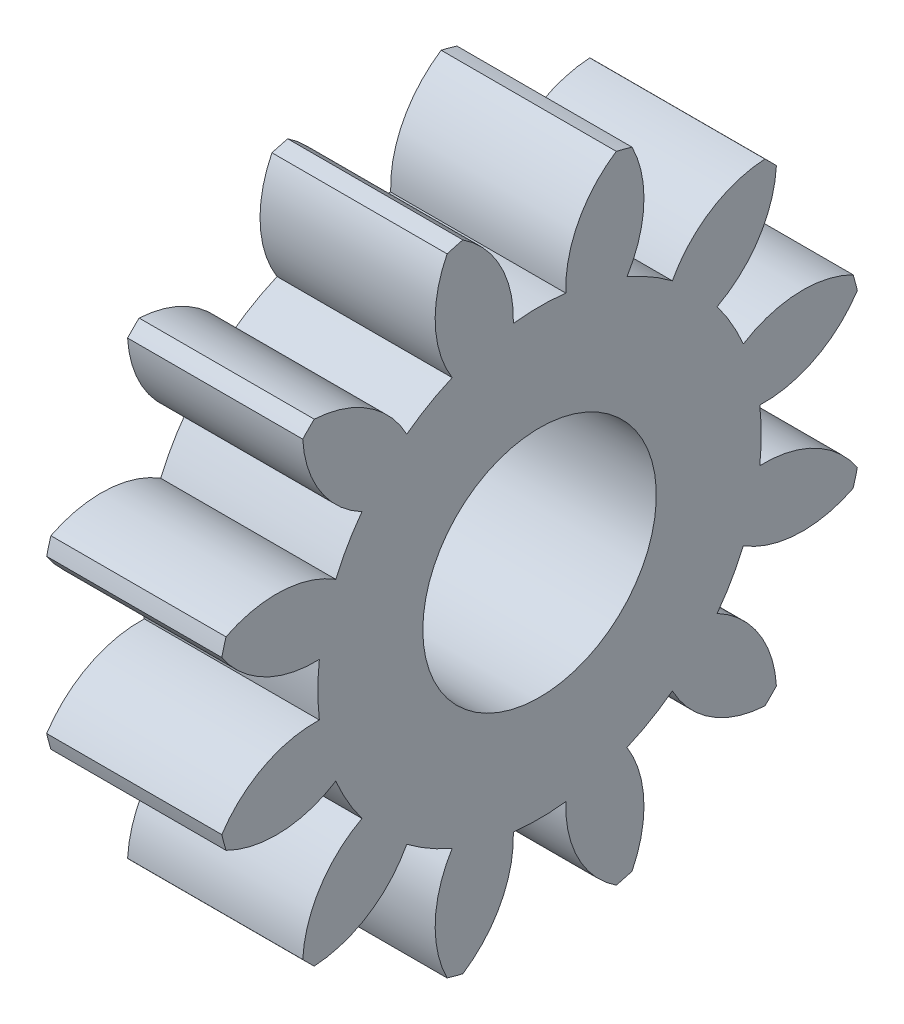
SolidWorks part; units mm, degrees
ref_plane "Plane1" through (0, 0, 0) normal (0, 0, 1) x (1, 0, 0)
ref_plane "Plane2" through (0, 0, 0) normal (0, 1, 0) x (1, 0, 0)
ref_plane "Plane3" through (0, 0, 0) normal (1, 0, 0) x (0, 0, -1)
sketch "HoldingSke" plane through (0, 0, 0) normal (0, 1, 0) x (1, 0, 0)
  line L0 (0, 0) -> (1.2227, -0.2599)
  line L1 (-15, 0) -> (100, 0) construction
  line L2 (0, 0) -> (-2.1039, 2.3779)
  line L3 (0, 0) -> (-11.863, 4.5341)
  line L4 (0, 0) -> (8.4473, 1.7955)
  line L5 (0, 0) -> (-46.8476, -17.4728)
  line L6 (0, 0) -> (-9.9476, -6.7116)
  line L7 (-2.1039, 2.3779) -> (8.6586, 51.2059)
  line L8 (-76.2, 54.61) -> (-75.5, 54.61)
  line L9 (-71.009, 38.7566) -> (-53.1078, 45.2721)
  line L10 (-76.2, 71.12) -> (104.1128, 71.12)
  line L11 (0, 0) -> (-12, 0)
  line L12 (-76.2, 101.6) -> (-76.17, 101.6)
  line L13 (24.9733, 27.94) -> (52.9518, 28.4284)
  line L14 (24.9733, 27.94) -> (24.9743, 27.94)
  line L15 (24.9733, 27.94) -> (100.4006, 29.5858)
  line L16 (-63.627, -0.8) -> (-12.827, -0.8)
  circle A0 centre (0, 0) radius 2
  circle A1 centre (0, 0) radius 3.799
  circle A2 centre (0, 0) radius 37.5
  circle A3 centre (0, 0) radius 2
  dimension "MHD" = 7.598
  dimension "Hub_dia" = 75
  dimension "Bore" = 4
  dimension "MBD" = 4
  dimension "Num_teeth" = 12
  dimension "Pitch" = 1.25
  dimension "Overall_len" = 50
  dimension "Show_teeth" = 12
  dimension "Thickness" = 12
  dimension "OAL" = 50.0001
  dimension "T_dim" = 0.7
  dimension "Ap" = 20
  dimension "H" = 19.05
  dimension "Pitch_radius" = 180.3128
  dimension "Width" = 12
  dimension "Backlash" = 0.03
  dimension "Addendum_fac" = 1
  dimension "Dedendum_fac" = 1.25
  dimension "Clearance_fac" = 0.25
  dimension "Dedendum_add" = 0.001
  dimension "Module" = 0.8
sketch "BasProSke" plane through (0, 0, 0) normal (0, 1, 0) x (1, 0, 0)
  line L0 (-10, 0) -> (60, 0) construction
  line L1 (0, 0) -> (0, 5.6)
  line L2 (0, 0) -> (12, 0)
  line L3 (12, 0) -> (12, 5.6)
  line L4 (12, 5.6) -> (0, 5.6)
  dimension "Thickness" = 12
  dimension "Diameter" = 11.2
revolve "Base-Revolve" add sketch "BasProSke" angle 360 about L0
sketch "TooCutSke" plane through (0, 0, 0) normal (1, 0, 0) x (0, 0, -1)
  line L1 (0, 0) -> (0, 107) construction
  line L2 (0, 0) -> (-0.6789, 4.7517) construction
  line L3 (0, 0) -> (-2.4668, 9.2063) construction
  line L4 (-0.6789, 4.7517) -> (-1.2334, 4.6032) construction
  arc A0 (0.4492, 3.7723) -> (-0.4492, 3.7723) centre (0, 0) ccw
  arc A1 (1.3434, 5.4626) -> (-1.3434, 5.4626) centre (0, 0) ccw
  circle A2 centre (0, 0) radius 4.8 construction
  circle A3 centre (0, 0) radius 4.5105 construction
  arc A4 (-0.4492, 3.7723) -> (-1.3434, 5.4626) centre (-2.3681, 3.8389) ccw
  arc A5 (1.3434, 5.4626) -> (0.4492, 3.7723) centre (2.3681, 3.8389) ccw
  dimension "Root_dia" = 7.598
  dimension "Overcut_dia" = 11.2508
  dimension "Pitch_dia" = 9.6
  dimension "Base_dia" = 9.021
  dimension "Flank_rad" = 1.92
  dimension "Half_ang" = 15
  dimension "Half_CT" = 0.574
extrude "ToothCut" cut sketch "TooCutSke" along normal through all
fillet "Breaks" [suppressed] radius 0.016
fillet "RootFillets" [suppressed] radius 0.201
pattern_circular "TeethCuts" count 12 every 30 about axis through (-10, 0, 0) along (1, 0, 0) of "ToothCut", "RootFillets", "Breaks"
sketch "HubNeaOneSke" plane through (0, 0, 0) normal (-1, 0, 0) x (0, 0, 1)
  circle A0 centre (0, 0) radius 3.799
  dimension "Diameter" = 7.598
extrude "HubNearOne" [suppressed] add sketch "HubNeaOneSke" along normal blind 38.0001
sketch "HubNeaBotSke" plane through (0, 0, 0) normal (-1, 0, 0) x (0, 0, 1)
  circle A0 centre (0, 0) radius 3.799
  dimension "Diameter" = 7.598
extrude "HubNearBoth" [suppressed] add sketch "HubNeaBotSke" along normal blind 19
ref_plane "FarPln" through (12, 0, 0) normal (1, 0, 0) x (0, 0, -1)
sketch "HubFarSke" plane through (12, 0, 0) normal (1, 0, 0) x (0, 0, -1)
  circle A0 centre (0, 0) radius 3.799
  dimension "Diameter" = 7.598
extrude "HubFar" [suppressed] add sketch "HubFarSke" along normal blind 19
sketch "BorSke" plane through (0, 0, 0) normal (1, 0, 0) x (0, 0, -1)
  circle A0 centre (0, 0) radius 2
  dimension "Diameter" = 4
extrude "Bore" cut sketch "BorSke" along normal mid plane 100.0001
sketch "KeySke" plane through (0, 0, 0) normal (1, 0, 0) x (0, 0, -1)
  line L0 (-0.8, 0) -> (-0.8, 2.7)
  line L1 (-0.8, 2.7) -> (0.8, 2.7)
  line L2 (0.8, 2.7) -> (0.8, 0)
  line L3 (0, 0) -> (0, 34) construction
  line L4 (-0.8, 0) -> (0.8, 0)
  dimension "Offset" = 2.7
  dimension "Width" = 1.6
extrude "Keyway" [suppressed] cut sketch "KeySke" along normal mid plane 100.0001
pattern_circular "Keyway2" [suppressed] count 2 every 90 about axis through (-10, 0, 0) along (1, 0, 0)
sketch "Croquis1" plane through (0, 0, 0) normal (-1, 0, 0) x (0, 0, 1)
  line L1 (-5.9657, 6.0317) -> (6.45, 6.0317)
  line L2 (-5.9657, 6.0317) -> (-5.9657, -5.7235)
  line L3 (-5.9657, -5.7235) -> (6.45, -5.7235)
  line L4 (6.45, 6.0317) -> (6.45, -5.7235)
extrude "Cortar-Extruir1" cut sketch "Croquis1" against normal blind 9
equation "' \"Module@HoldingSke\" = 6.35"
equation "' \"Num_teeth@HoldingSke\" = 12"
equation "' \"Ap@HoldingSke\" =  20"
equation "' \"Ap@HoldingSke\" = 20"
equation "' \"Width@HoldingSke\" = 0.5 * 25.4"
equation "' \"Hub_dia@HoldingSke\"= 1 * 25.4"
equation "' \"Hub_dia@HoldingSke\" = 1 * 25.4"
equation "' \"Overall_len@HoldingSke\" = 1.0 * 25.4"
equation "' \"Bore@HoldingSke\" = 0.75 * 25.4"
equation "' \"T_dim@HoldingSke\" = 0.1 * 25.4"
equation "' \"Width@KeySke\" = 0.25 * 25.4"
equation "' \"Show_teeth@HoldingSke\" = 13"
equation "' \"Backlash@HoldingSke\" = 0.009 * 25.4"
equation "' \"Addendum_fac@HoldingSke\" = 1.0"
equation "' \"Dedendum_fac@HoldingSke\" = 1.25"
equation "' \"Dedendum_add@HoldingSke\" = 0.00005 * 25.4"
equation "' \"Clearance_fac@HoldingSke\" = 0.25"
equation "\"Pitch@HoldingSke\" = 1 / \"Module@HoldingSke\""
equation "\"Overcut_dia@TooCutSke\" = (\"Num_teeth@HoldingSke\" + 2 * \"Addendum_fac@HoldingSke\") / \"Pitch@HoldingSke\" + 0.002 * 25.4"
equation "\"Pitch_dia@TooCutSke\" = \"Num_teeth@HoldingSke\" / \"Pitch@HoldingSke\""
equation "\"Base_dia@TooCutSke\" = \"Num_teeth@HoldingSke\" / \"Pitch@HoldingSke\" * cos((\"Ap@HoldingSke\"  * 3.14159265 / 180))"
equation "\"Root_dia@TooCutSke\" = (\"Num_teeth@HoldingSke\" + 2) / \"Pitch@HoldingSke\" - 2 * (\"Addendum_fac@HoldingSke\" + \"Dedendum_fac@HoldingSke\") / \"Pitch@HoldingSke\" - \"Dedendum_add@HoldingSke\" * 2"
equation "\"Half_ang@TooCutSke\" = 180 / \"Num_teeth@HoldingSke\""
equation "\"Half_CT@TooCutSke\" = \"Num_teeth@HoldingSke\" / \"Pitch@HoldingSke\" * sin((3.14159265 / 2 / \"Num_teeth@HoldingSke\")) / 2 - 7 * \"Backlash@HoldingSke\" / 4"
equation "\"Flank_rad@TooCutSke\" = \"Num_teeth@HoldingSke\" / \"Pitch@HoldingSke\" / 5"
equation "\"Radius@RootFillets\" = \"Clearance_fac@HoldingSke\" / \"Pitch@HoldingSke\" + \"Dedendum_add@HoldingSke\""
equation "\"Break_rad@Breaks\" = 0.02 / \"Pitch@HoldingSke\""
equation "\"Thickness@HoldingSke\" = \"Width@HoldingSke\""
equation "\"OAL@HoldingSke\" = \"Thickness@HoldingSke\""
equation "\"MHD@HoldingSke\" = (\"Num_teeth@HoldingSke\" + 2) / \"Pitch@HoldingSke\" - 2 * (\"Addendum_fac@HoldingSke\" + \"Dedendum_fac@HoldingSke\")  / \"Pitch@HoldingSke\" - \"Dedendum_add@HoldingSke\" * 2"
equation "\"MBD@HoldingSke\" = (\"Num_teeth@HoldingSke\" + 2) / \"Pitch@HoldingSke\" - 2 * (\"Addendum_fac@HoldingSke\" + \"Dedendum_fac@HoldingSke\")  / \"Pitch@HoldingSke\" - \"Dedendum_add@HoldingSke\" * 2 - 0.002 * 25.4"
equation "\"MHD@HoldingSke\" = ((sgn( \"MHD@HoldingSke\" - \"Hub_dia@HoldingSke\" )-1)*( \"MHD@HoldingSke\" - \"Hub_dia@HoldingSke\" ))/-2+ \"Hub_dia@HoldingSke\""
equation "\"MBD@HoldingSke\" = ((sgn( \"MBD@HoldingSke\" - \"Bore@HoldingSke\" )-1)*( \"MBD@HoldingSke\" - \"Bore@HoldingSke\" ))/-2+ \"Bore@HoldingSke\""
equation "\"OAL@HoldingSke\" = ((sgn( \"OAL@HoldingSke\" - \"Overall_len@HoldingSke\" )+1)*( \"OAL@HoldingSke\" - \"Overall_len@HoldingSke\" ))/2 + \"Overall_len@HoldingSke\" + 0.000002 * 25.4"
equation "\"Num_teeth@TeethCuts\" = int( \"Show_teeth@HoldingSke\" ) + 1"
equation "\"Num_teeth@TeethCuts\" = ((sgn( \"Num_teeth@TeethCuts\" - \"Num_teeth@HoldingSke\" )-1)*( \"Num_teeth@TeethCuts\" - \"Num_teeth@HoldingSke\" ))/-2+ \"Num_teeth@HoldingSke\""
equation "\"Num_teeth@TeethCuts\" = ((sgn( \"Num_teeth@TeethCuts\" - 2.0)+1)*( \"Num_teeth@TeethCuts\" - 2.0))/2 +2.0"
equation "\"Angle@TeethCuts\" = 360.0 / \"Num_teeth@HoldingSke\""
equation "\"Diameter@BasProSke\" = (\"Num_teeth@HoldingSke\" + 2 * \"Addendum_fac@HoldingSke\") / \"Pitch@HoldingSke\""
equation "\"Thickness@BasProSke\"  = \"Thickness@HoldingSke\""
equation "' \"Fillet_rad@BasProSke\" =  \"Thickness@HoldingSke\" * 0.05"
equation "' \"Fillet_rad@BasProSke\" = \"Thickness@HoldingSke\" * 0.05"
equation "\"MHD@HoldingSke\" = ((sgn( \"MHD@HoldingSke\" - \"Root_dia@TooCutSke\" )-1)*( \"MHD@HoldingSke\" - \"Root_dia@TooCutSke\" ))/-2+ \"Root_dia@TooCutSke\""
equation "\"Diameter@HubNeaOneSke\" = \"MHD@HoldingSke\""
equation "\"Length@HubNearOne\" = \"OAL@HoldingSke\" - \"Thickness@BasProSke\""
equation "\"Diameter@HubNeaBotSke\" = \"MHD@HoldingSke\""
equation "\"Length@HubNearBoth\" = ( \"OAL@HoldingSke\" - \"Thickness@BasProSke\" ) / 2.0"
equation "\"Thickness@FarPln\" = \"Thickness@BasProSke\""
equation "\"Diameter@HubFarSke\" = \"MHD@HoldingSke\""
equation "\"Length@HubFar\" = ( \"OAL@HoldingSke\" - \"Thickness@BasProSke\" ) / 2.0"
equation "\"Diameter@BorSke\" = \"MBD@HoldingSke\""
equation "\"D1@Bore\" = \"OAL@HoldingSke\" * 2.0"
equation "\"D1@Keyway\" = \"OAL@HoldingSke\" * 2.0"
equation "\"Offset@KeySke\" = \"T_dim@HoldingSke\" + \"MBD@HoldingSke\" / 2.0"
